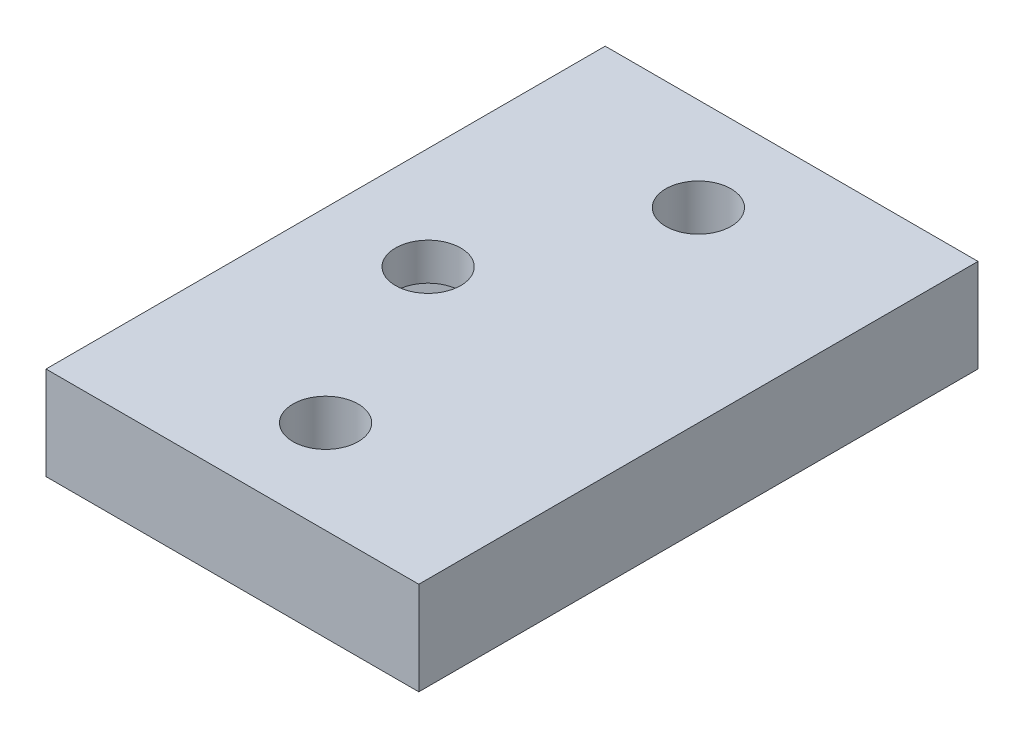
SolidWorks part; units mm, degrees
material "ABS"
ref_plane "Front Plane" through (0, 0, 0) normal (0, 0, 1) x (1, 0, 0)
ref_plane "Top Plane" through (0, 0, 0) normal (0, 1, 0) x (1, 0, 0)
ref_plane "Right Plane" through (0, 0, 0) normal (1, 0, 0) x (0, 0, -1)
sketch "Sketch1" plane through (0, 0, 0) normal (0, 1, 0) x (1, 0, 0)
  line L1 (0, 0) -> (20, 0)
  line L2 (0, 0) -> (0, 30)
  line L3 (0, 30) -> (20, 30)
  line L4 (20, 0) -> (20, 30)
  dimension "D1" = 20
  dimension "D2" = 30
extrude "Boss-Extrude1" add sketch "Sketch1" along normal blind 5
sketch "Sketch2" plane through (0, 5, 0) normal (0, 1, 0) x (1, 0, 0)
  line L0 (0, 0) -> (20, 0) construction
  line L1 (0, 30) -> (0, 0) construction
  circle A0 centre (5.5, 15) radius 1.75
  dimension "D1" = 3.5
  dimension "D2" = 15
  dimension "D3" = 5.5
extrude "Cut-Extrude1" cut sketch "Sketch2" against normal blind 8
sketch "Sketch3" plane through (0, 5, 0) normal (0, 1, 0) x (1, 0, 0)
  line L0 (20, 30) -> (0, 30) construction
  line L1 (0, 30) -> (0, 0) construction
  line L2 (0, 0) -> (20, 0) construction
  circle A0 centre (10, 25) radius 1.75
  circle A1 centre (10, 5) radius 1.75
  dimension "D1" = 3.5
  dimension "D4" = 3.5
  dimension "D2" = 5
  dimension "D3" = 10
  dimension "D5" = 5
extrude "Cut-Extrude2" cut sketch "Sketch3" against normal through all
sketch "Sketch4" plane through (0, 0, 0) normal (-1, 0, 0) x (0, 0, 1)
  line L1 (-18, 0) -> (-12, 0)
  line L2 (-18, 0) -> (-18, 3)
  line L3 (-18, 3) -> (-12, 3)
  line L4 (-12, 0) -> (-12, 3)
  line L5 (-30, 5) -> (-30, 0) construction
  dimension "D1" = 3
  dimension "D2" = 6
  dimension "D3" = 12
extrude "Cut-Extrude3" cut sketch "Sketch4" against normal blind 9
